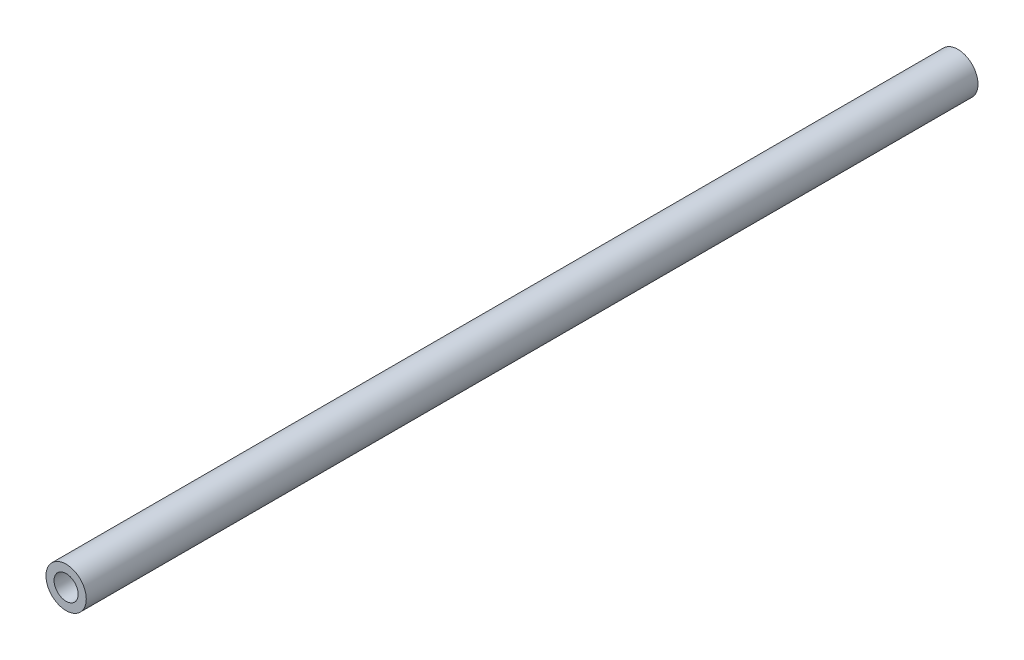
SolidWorks part; units mm, degrees
material "AISI 1020"
ref_plane "Front Plane" through (0, 0, 0) normal (0, 0, 1) x (1, 0, 0)
ref_plane "Top Plane" through (0, 0, 0) normal (0, 1, 0) x (1, 0, 0)
ref_plane "Right Plane" through (0, 0, 0) normal (1, 0, 0) x (0, 0, -1)
sketch "Sketch1" plane through (0, 0, 0) normal (0, 0, 1) x (1, 0, 0)
  circle A0 centre (0, 0) radius 3.175
  circle A1 centre (0, 0) radius 1.8986
  dimension "D1" = 6.35
  dimension "D2" = 3.7973
extrude "Boss-Extrude1" add sketch "Sketch1" along normal blind 140.4938
